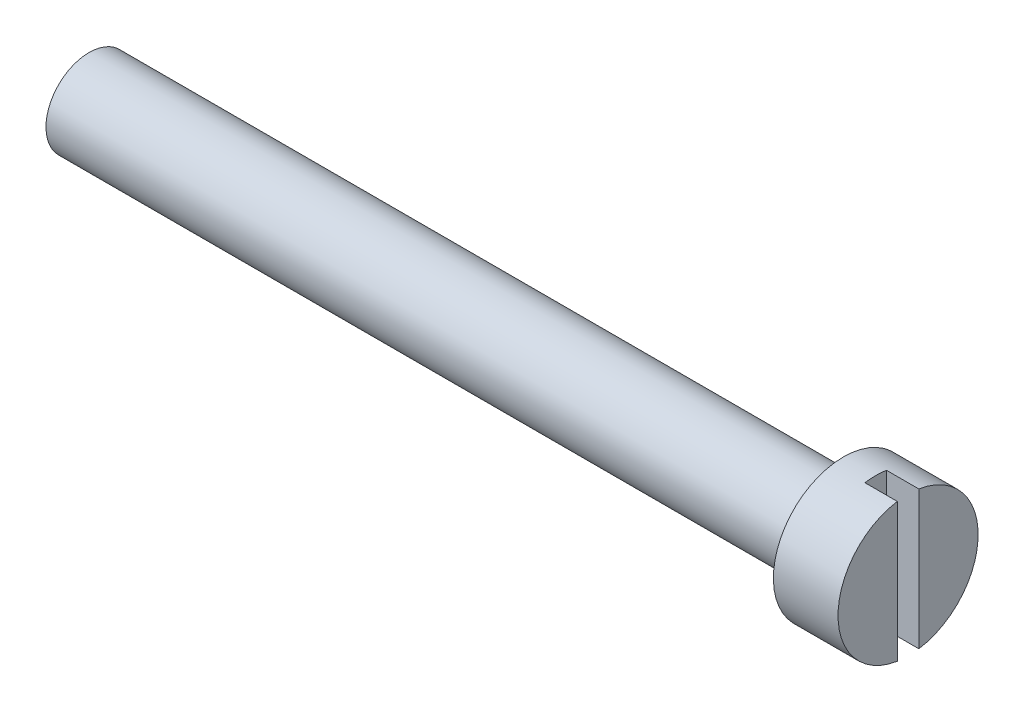
SolidWorks part; units mm, degrees
material "AISI 316 Stainless Steel Sheet (SS)"
ref_plane "Front Plane" through (0, 0, 0) normal (0, 0, 1) x (1, 0, 0)
ref_plane "Top Plane" through (0, 0, 0) normal (0, 1, 0) x (1, 0, 0)
ref_plane "Right Plane" through (0, 0, 0) normal (1, 0, 0) x (0, 0, -1)
sketch "Sketch1" plane through (0, 0, 0) normal (0, 0, 1) x (1, 0, 0)
  line L0 (0, 0) -> (-38, 0)
  line L1 (-38, 0) -> (-38, 2)
  line L2 (-38, 2) -> (-3, 2)
  line L3 (-3, 2) -> (-3, 3.25)
  line L4 (-3, 3.25) -> (0, 3.25)
  line L5 (0, 3.25) -> (0, 0)
  dimension "D1" = 3
  dimension "D2" = 35
  dimension "D3" = 2
  dimension "D4" = 3.25
revolve "Revolve1" add sketch "Sketch1" angle 360 about L0
sketch "Sketch2" plane through (0, 0, 0) normal (1, 0, 0) x (0, 0, -1)
  line L1 (-0.5, -3.25) -> (0.5, -3.25)
  line L2 (-0.5, -3.25) -> (-0.5, 3.25)
  line L3 (-0.5, 3.25) -> (0.5, 3.25)
  line L4 (0.5, -3.25) -> (0.5, 3.25)
  line L5 (-0.5, -3.25) -> (0.5, 3.25) construction
  line L6 (-0.5, 3.25) -> (0.5, -3.25) construction
  circle A0 centre (0, 0) radius 3.25 construction
  point P0 (0, 0)
  dimension "D1" = 1
extrude "Cut-Extrude1" cut sketch "Sketch2" against normal blind 1.5
